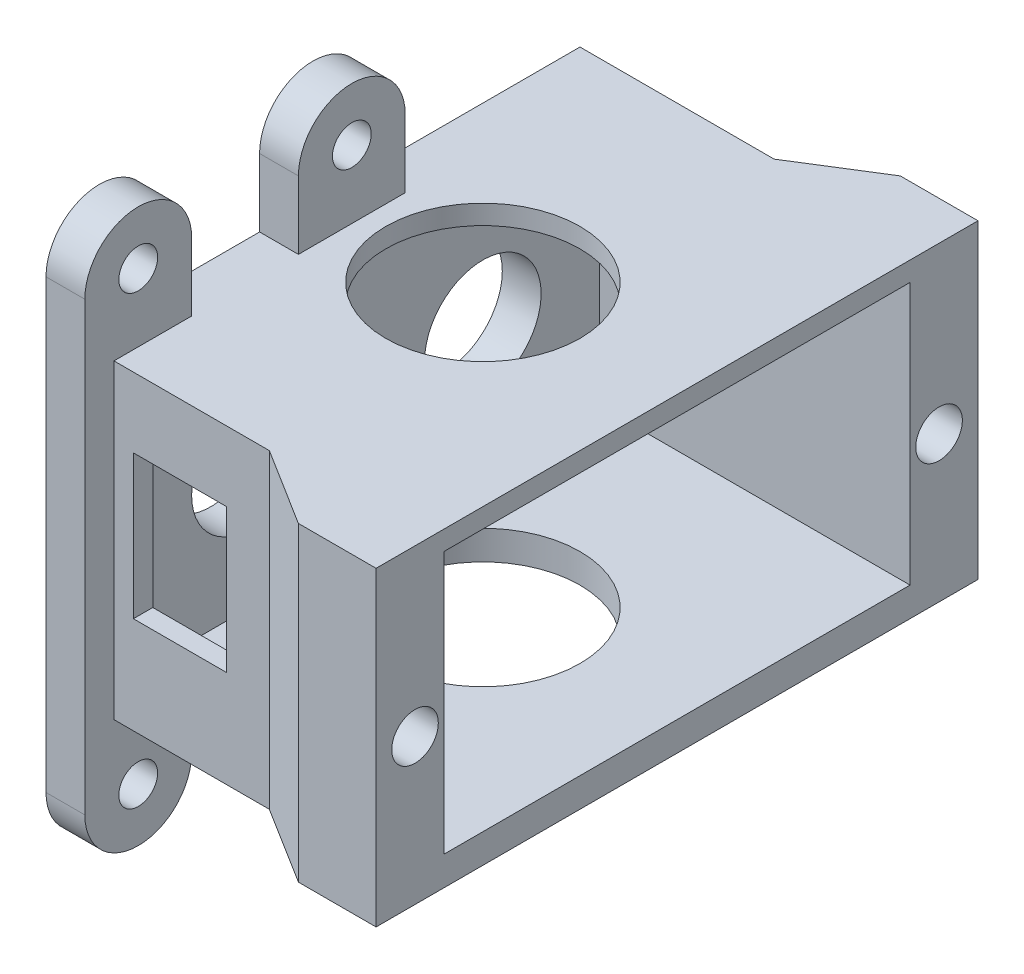
SolidWorks part; units mm, degrees
ref_plane "Front Plane" through (0, 0, 0) normal (0, 0, 1) x (1, 0, 0)
ref_plane "Top Plane" through (0, 0, 0) normal (0, 1, 0) x (1, 0, 0)
ref_plane "Right Plane" through (0, 0, 0) normal (1, 0, 0) x (0, 0, -1)
sketch "Sketch2" plane through (0, 0, 0) normal (0, 1, 0) x (1, 0, 0)
  line L1 (-65, 65) -> (65, 65)
  line L2 (-65, 65) -> (-65, -65)
  line L3 (-65, -65) -> (65, -65)
  line L4 (65, 65) -> (65, -65)
  line L5 (-65, 65) -> (65, -65) construction
  line L6 (-65, -65) -> (65, 65) construction
  point P0 (0, 0)
  dimension "D1" = 130
  dimension "D2" = 130
extrude "Boss-Extrude2" add sketch "Sketch2" along normal mid plane 75
sketch "Sketch3" plane through (0, 37.5, 0) normal (0, 1, 0) x (1, 0, 0)
  line L0 (65, -65) -> (65, 65) construction
  line L1 (65, 60) -> (-15, 60)
  line L2 (65, 60) -> (65, -60)
  line L3 (65, -60) -> (-15, -60)
  line L4 (-15, 60) -> (-15, -60)
  line L5 (65, 65) -> (-65, 65) construction
  dimension "D1" = 5
  dimension "D2" = 80
  dimension "D3" = 120
extrude "Cut-Extrude1" cut sketch "Sketch3" against normal blind 67.5
sketch "Sketch15" plane through (0, 37.5, 0) normal (0, 1, 0) x (1, 0, 0)
  line L0 (-15, 60) -> (-15, -60) construction
  line L1 (-25, 80.9743) -> (-106.5937, 80.9743)
  line L2 (-25, 80.9743) -> (-25, -90.5495)
  line L3 (-25, -90.5495) -> (-106.5937, -90.5495)
  line L4 (-106.5937, 80.9743) -> (-106.5937, -90.5495)
  line L5 (65, 65) -> (-65, 65) construction
  dimension "D1" = 10
  dimension "D2" = 15.9743
  dimension "D3" = 81.5937
extrude "Cut-Extrude9" cut sketch "Sketch15" against normal through all
sketch "Sketch5" plane through (65, 0, 0) normal (1, 0, 0) x (0, 0, -1)
  line L0 (-65, -37.5) -> (65, -37.5) construction
  line L1 (-65, 37.5) -> (-77.5, 37.5)
  line L2 (-65, 37.5) -> (-65, -37.5)
  line L3 (-65, -37.5) -> (-77.5, -37.5)
  line L4 (-77.5, 37.5) -> (-77.5, -37.5)
  line L5 (0, 128.1534) -> (0, -57.4338) construction
  line L6 (65, -37.5) -> (77.5, -37.5)
  line L7 (77.5, 37.5) -> (77.5, -37.5)
  line L8 (65, 37.5) -> (77.5, 37.5)
  line L9 (65, 37.5) -> (65, -37.5)
  dimension "D1" = 12.5
extrude "Boss-Extrude4" add sketch "Sketch5" against normal blind 20 separate body
sketch "Sketch7" plane through (65, 0, 0) normal (1, 0, 0) x (0, 0, -1)
  line L0 (0, 109.6471) -> (0, -63.9441) construction
  line L1 (-77.5, 37.5) -> (-77.5, -37.5) construction
  circle A0 centre (-67.475, 0) radius 6
  circle A1 centre (67.475, 0) radius 6
  point P7 (-77.5, 0)
  dimension "D1" = 12
  dimension "D2" = 134.95
extrude "Cut-Extrude10" cut sketch "Sketch7" against normal up to surface (20 mm away) up to face at (45, 0, -71.25)
sketch "Sketch16" plane through (0, 37.5, 0) normal (0, 1, 0) x (1, 0, 0)
  line L0 (-25, 65) -> (-25, -65)
  line L1 (-25, -65) -> (45, -65)
  line L2 (45, -65) -> (45, -77.5)
  line L3 (45, -77.5) -> (65, -77.5)
  line L4 (65, -77.5) -> (65, 77.5)
  line L5 (65, 77.5) -> (45, 77.5)
  line L6 (45, 77.5) -> (45, 65)
  line L7 (45, 65) -> (-25, 65)
extrude "Boss-Extrude7" add sketch "Sketch16" along normal blind 5
sketch "Sketch17" plane through (0, 0, 65) normal (0, 0, 1) x (1, 0, 0)
  line L1 (-10, 24.5) -> (14, 24.5)
  line L2 (-10, 24.5) -> (-10, -12.5)
  line L3 (-10, -12.5) -> (14, -12.5)
  line L4 (14, 24.5) -> (14, -12.5)
  line L5 (-25, 42.5) -> (-25, -37.5) construction
  line L7 (-25, -37.5) -> (45, -37.5) construction
  dimension "D1" = 15
  dimension "D2" = 24
  dimension "D3" = 37
  dimension "D4" = 25
extrude "Cut-Extrude11" cut sketch "Sketch17" against normal up to surface (5 mm away) up to face at (25, 3.75, 60)
sketch "Sketch18" plane through (-25, 0, 0) normal (-1, 0, 0) x (0, 0, 1)
  line L0 (45, 42.5) -> (45, 60)
  line L1 (-65, 42.5) -> (65, 42.5) construction
  line L3 (72.5, 60) -> (72.5, 42.5)
  line L4 (65, 42.5) -> (77.5, 42.5) construction
  line L5 (72.5, 42.5) -> (45, 42.5)
  line L6 (65, 2.5) -> (-82.141, 2.5) construction
  line L7 (65, 42.5) -> (65, -37.5) construction
  line L8 (72.5, -37.5) -> (45, -37.5)
  line L9 (72.5, -55) -> (72.5, -37.5)
  line L10 (45, -37.5) -> (45, -55)
  arc A0 (45, 60) -> (72.5, 60) centre (58.75, 60) cw
  circle A1 centre (58.75, 60) radius 5
  circle A2 centre (58.75, -55) radius 5
  arc A3 (45, -55) -> (72.5, -55) centre (58.75, -55) ccw
  dimension "D4" = 10
  dimension "D1" = 27.5
  dimension "D2" = 110
  dimension "D3" = 115
extrude "Boss-Extrude8" add sketch "Sketch18" against normal blind 10
pattern_linear "LPattern2" count 2 spacing 55 along (0, 0, -1) of "Boss-Extrude8"
ref_plane "Plane2" through (20, 0, 0) normal (-1, 0, 0) x (0, 0, 1)
sketch "Sketch20" plane through (0, 42.5, 0) normal (0, 1, 0) x (1, 0, 0)
  line L2 (-25, 65) -> (-25, 10) construction
  circle A0 centre (15, 0) radius 25
  dimension "D1" = 50
  dimension "D2" = 40
extrude "Cut-Extrude12" cut sketch "Sketch20" against normal up to surface (80 mm away) up to face at (10.7143, -37.5, 7.5)
sketch "Sketch21" plane through (-25, 0, 0) normal (-1, 0, 0) x (0, 0, 1)
  line L0 (0, 106.9544) -> (0, -96.5794) construction
  line L2 (17.5, 42.5) -> (45, 42.5) construction
  circle A0 centre (30, 2.5) radius 15
  circle A1 centre (-30, 2.5) radius 15
  dimension "D1" = 30
  dimension "D2" = 30
  dimension "D3" = 40
extrude "Cut-Extrude13" cut sketch "Sketch21" against normal up to surface (10 mm away) up to face at (-15, 3.75, 0)
sketch "Sketch22" plane through (0, 42.5, 0) normal (0, 1, 0) x (1, 0, 0)
  line L0 (45, -65) -> (45, -77.5)
  line L2 (45, 77.5) -> (45, 65)
  line L3 (45, 65) -> (25, 65)
  line L4 (45, 65) -> (-25, 65) construction
  line L5 (25, 65) -> (45, 77.5)
  line L6 (45, -77.5) -> (25, -65)
  line L7 (-15, -65) -> (45, -65) construction
  line L8 (25, -65) -> (45, -65)
  dimension "D1" = 20
  dimension "D2" = 20
extrude "Boss-Extrude9" add sketch "Sketch22" against normal up to surface (80 mm away) up to face at (15, -37.5, -25)
sketch "Sketch23" plane through (0, 42.5, 0) normal (0, -1, 0) x (-1, 0, 0)
  line L0 (25, -72.5) -> (15, -72.5)
  line L1 (15, -72.5) -> (15, -65)
  line L2 (15, -65) -> (25, -65)
  line L3 (25, -65) -> (25, -72.5)
extrude "Boss-Extrude10" add sketch "Sketch23" along normal up to surface (80 mm away) up to face at (-20, -37.5, 68.75)
